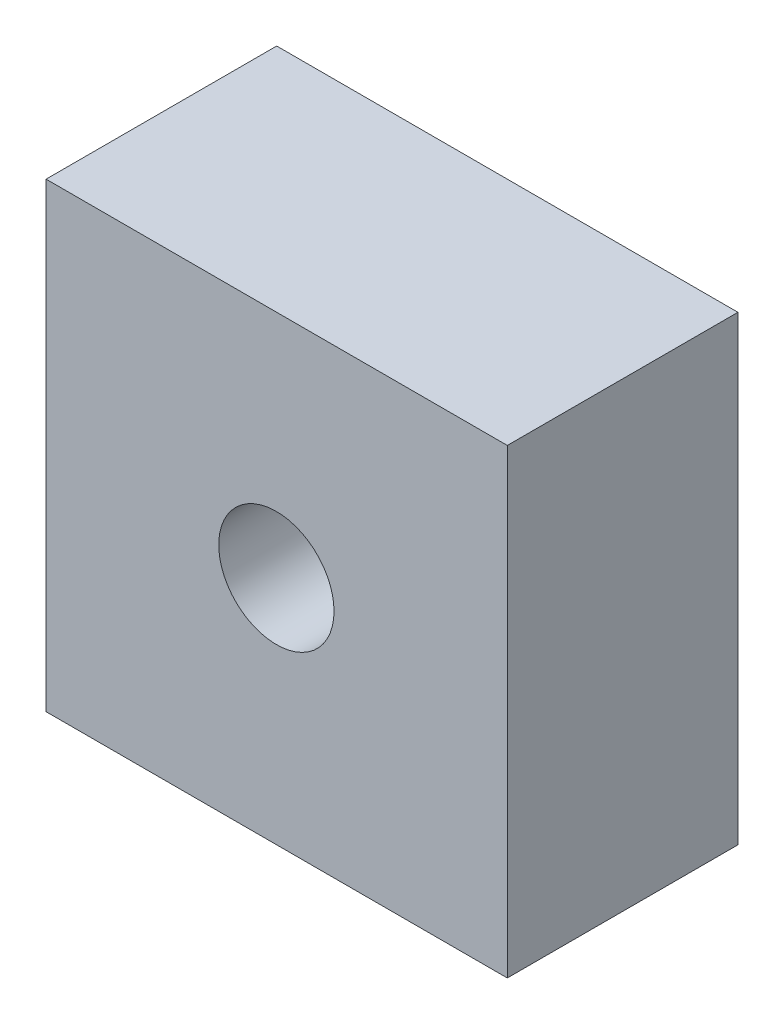
SolidWorks part; units mm, degrees
ref_plane "前视基准面" through (0, 0, 0) normal (0, 0, 1) x (1, 0, 0)
ref_plane "上视基准面" through (0, 0, 0) normal (0, 1, 0) x (1, 0, 0)
ref_plane "右视基准面" through (0, 0, 0) normal (1, 0, 0) x (0, 0, -1)
other "Configuration Table"
sketch "草图1" plane through (0, 0, 0) normal (0, 0, 1) x (1, 0, 0)
  line L1 (0, 0) -> (20, 0)
  line L2 (0, 0) -> (0, 20)
  line L3 (0, 20) -> (20, 20)
  line L4 (20, 0) -> (20, 20)
extrude "BaseBox" add sketch "草图1" along normal blind 10
hole_wizard "M6 螺纹孔1" positions "草图3" profile "草图2" tap size "M6" standard "ISO"
sketch "草图3" plane through (0, 0, 10) normal (0, 0, 1) x (1, 0, 0)
  point P0 (9.9865, 10.0143)
sketch "草图2" plane through (9.9865, 10.0143, 10) normal (1, 0, 0) x (0, -1, 0)
  line L0 (0, 0) -> (0, 10)
  line L1 (0, 10) -> (2.5, 10)
  line L2 (2.5, 10) -> (2.5, 0)
  line L5 (2.5, 0) -> (0, 0)
  line L11 (0, -6.35) -> (0, 107.95) construction
  dimension "通孔螺纹孔钻头直径" = 5
  dimension "通孔螺纹孔钻头深度" = 10
cosmetic thread "孔螺纹线1" parameters "D1"=12, "D2"=6
